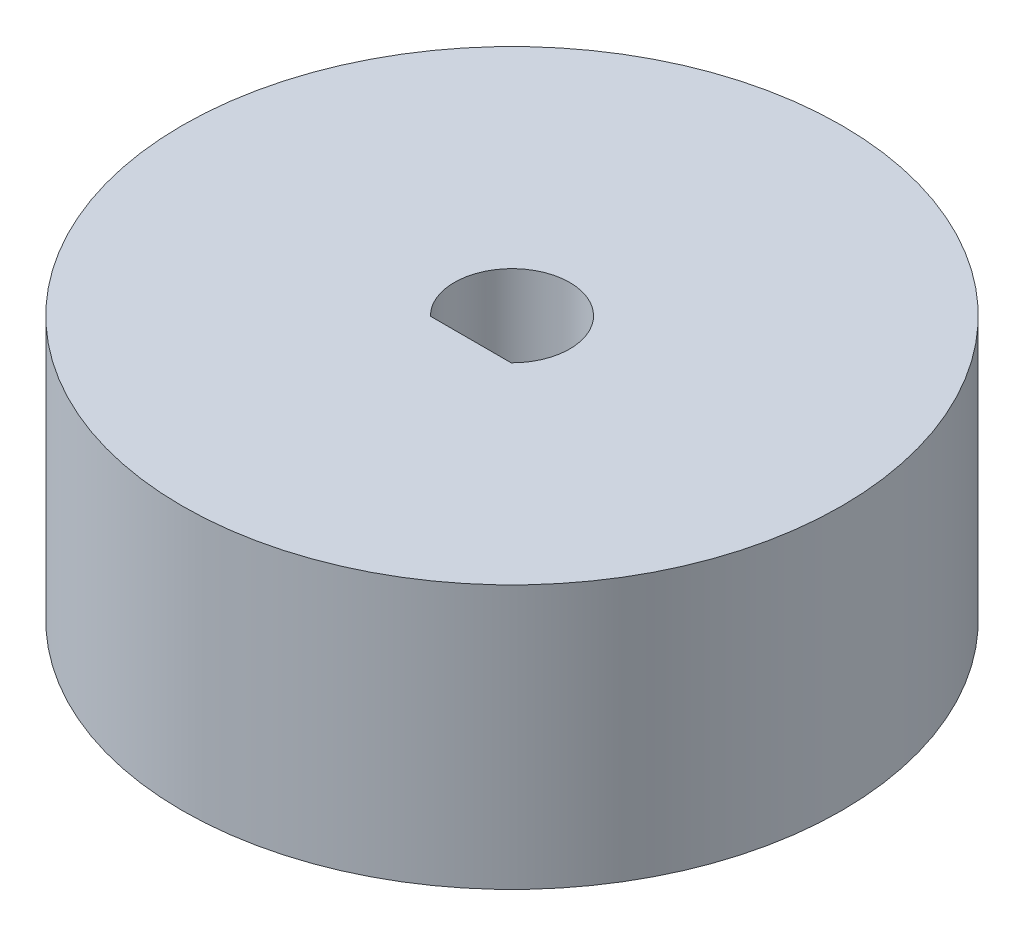
SolidWorks part; units mm, degrees
ref_plane "Front Plane" through (0, 0, 0) normal (0, 0, 1) x (1, 0, 0)
ref_plane "Top Plane" through (0, 0, 0) normal (0, 1, 0) x (1, 0, 0)
ref_plane "Right Plane" through (0, 0, 0) normal (1, 0, 0) x (0, 0, -1)
sketch "Sketch1" plane through (0, 0, 0) normal (0, 1, 0) x (1, 0, 0)
  circle A0 centre (0, 0) radius 12.7
extrude "Boss-Extrude1" add sketch "Sketch1" along normal blind 10.16
sketch "Sketch2" plane through (0, 10.16, 0) normal (0, 1, 0) x (1, 0, 0)
  line L0 (0, 2.2225) -> (0, -1.5875) construction
  line L1 (-1.5554, -1.5875) -> (1.5554, -1.5875)
  arc A0 (1.5554, -1.5875) -> (-1.5554, -1.5875) centre (0, 0) ccw
extrude "Cut-Extrude1" cut sketch "Sketch2" against normal through all
